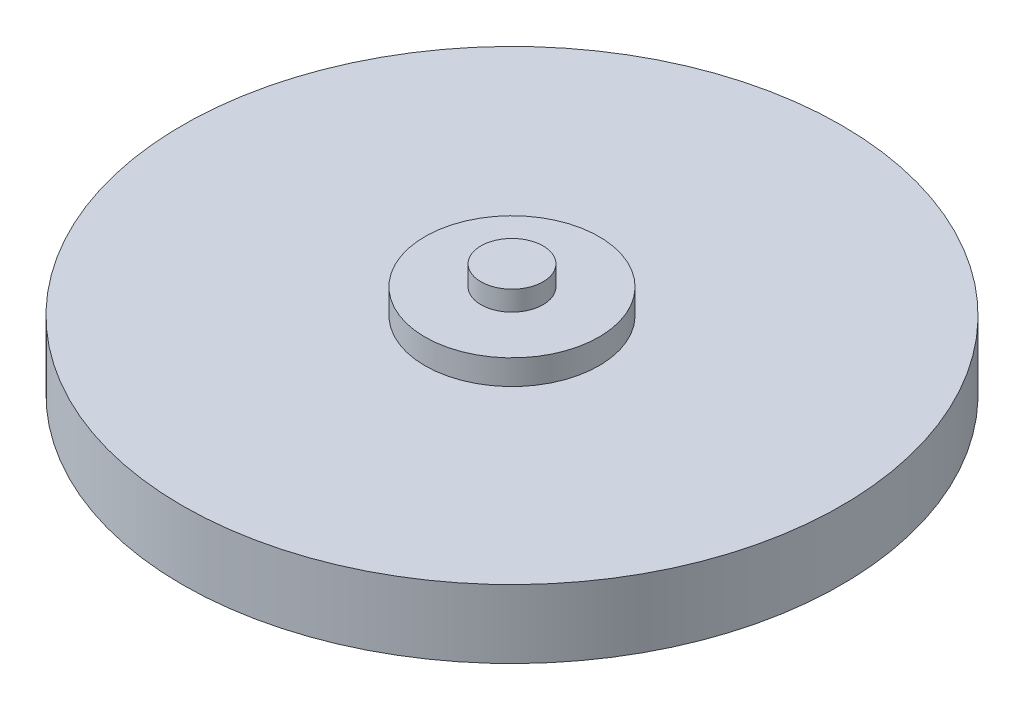
SolidWorks part; units mm, degrees
ref_plane "Front Plane" through (0, 0, 0) normal (0, 0, 1) x (1, 0, 0)
ref_plane "Top Plane" through (0, 0, 0) normal (0, 1, 0) x (1, 0, 0)
ref_plane "Right Plane" through (0, 0, 0) normal (1, 0, 0) x (0, 0, -1)
sketch "Sketch1" plane through (0, 0, 0) normal (0, 1, 0) x (1, 0, 0)
  circle A0 centre (0, 0) radius 26.5
  dimension "D1" = 53
extrude "Boss-Extrude1" add sketch "Sketch1" along normal blind 3.5
sketch "Sketch2" plane through (0, 3.5, 0) normal (0, 1, 0) x (1, 0, 0)
  circle A0 centre (0, 0) radius 7
  dimension "D1" = 14
extrude "Boss-Extrude2" add sketch "Sketch2" along normal blind 2
sketch "Sketch5" plane through (0, 5.5, 0) normal (0, 1, 0) x (1, 0, 0)
  circle A0 centre (0, 0) radius 2.5
  dimension "D1" = 5
extrude "Boss-Extrude3" add sketch "Sketch5" along normal blind 1.6
sketch "Sketch6" plane through (0, 0, 0) normal (0, -1, 0) x (1, 0, 0)
  circle A0 centre (0, 0) radius 26.5
  circle A1 centre (0, 0) radius 25
  dimension "D1" = 50
extrude "Boss-Extrude4" add sketch "Sketch6" along normal blind 2
